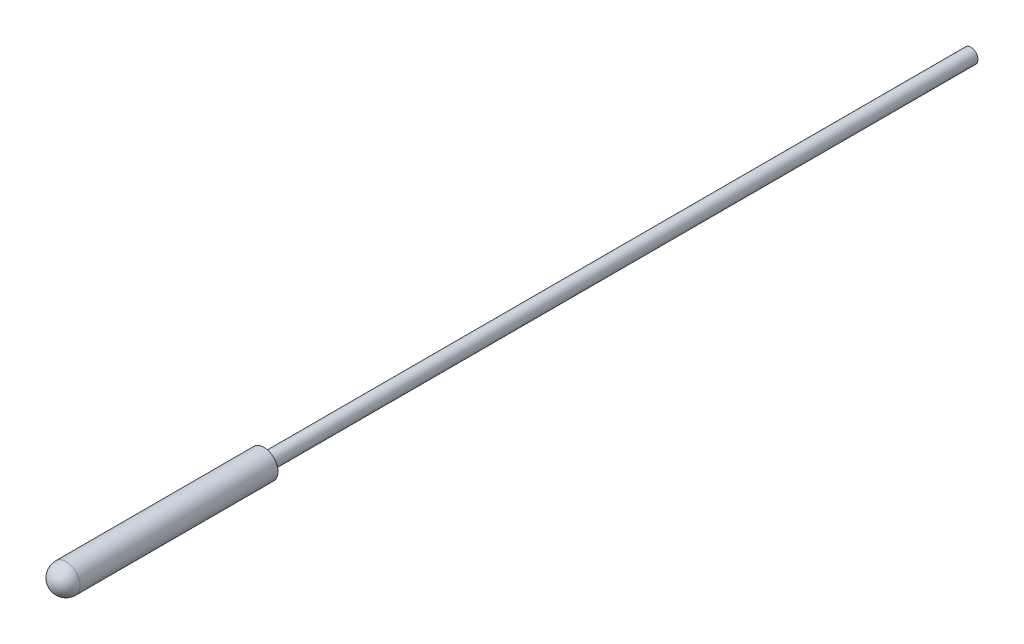
SolidWorks part; units mm, degrees
ref_plane "Front Plane" through (0, 0, 0) normal (0, 0, 1) x (1, 0, 0)
ref_plane "Top Plane" through (0, 0, 0) normal (0, 1, 0) x (1, 0, 0)
ref_plane "Right Plane" through (0, 0, 0) normal (1, 0, 0) x (0, 0, -1)
sketch "Sketch1" plane through (0, 0, 0) normal (0, 0, 1) x (1, 0, 0)
  circle A0 centre (0, 0) radius 2
extrude "Boss-Extrude1" add sketch "Sketch1" along normal blind 30
fillet "Fillet1" radius 2 1 edges at (2, 0, 30)
sketch "Sketch2" plane through (0, 0, 0) normal (0, 0, -1) x (-1, 0, 0)
  circle A0 centre (0, 0) radius 1.0146
extrude "Boss-Extrude2" add sketch "Sketch2" along normal blind 100
